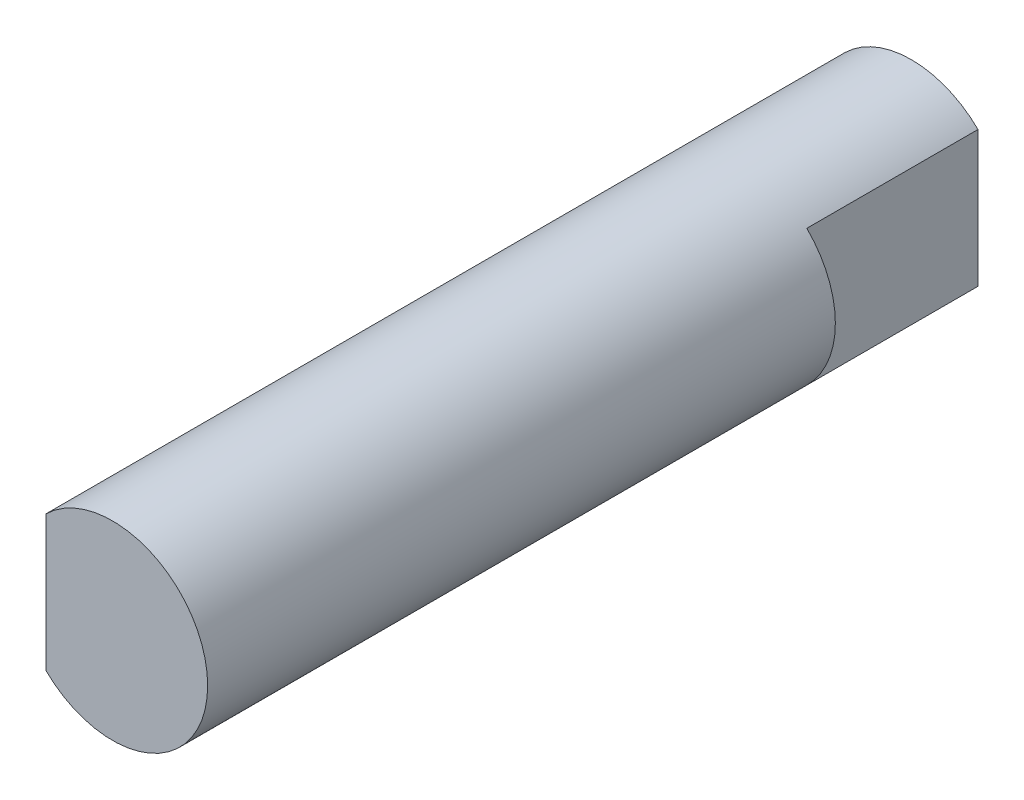
SolidWorks part; units mm, degrees
material "Cast Alloy Steel"
ref_plane "Front" through (0, 0, 0) normal (0, 0, 1) x (1, 0, 0)
ref_plane "Top" through (0, 0, 0) normal (0, 1, 0) x (1, 0, 0)
ref_plane "Right" through (0, 0, 0) normal (1, 0, 0) x (0, 0, -1)
sketch "Sketch1" plane through (0, 0, 0) normal (0, 0, 1) x (1, 0, 0)
  circle A0 centre (0, 0) radius 2.5
  dimension "D1" = 5
extrude "Boss-Extrude1" add sketch "Sketch1" along normal blind 21
sketch "Sketch2" plane through (0, 0, 0) normal (0, 0, -1) x (-1, 0, 0)
  line L2 (-1.75, -1.7854) -> (-1.75, 1.7854)
  line L4 (1.75, -1.7854) -> (1.75, 1.7854)
  line L5 (-1.75, -1.7854) -> (1.75, 1.7854) construction
  line L6 (-1.75, 1.7854) -> (1.75, -1.7854) construction
  circle A0 centre (0, 0) radius 2.5 construction
  arc A1 (-1.75, 1.7854) -> (-1.75, -1.7854) centre (0, 0) ccw
  arc A2 (1.75, 1.7854) -> (1.75, -1.7854) centre (0, 0) cw
  point P0 (0, 0)
  dimension "D1" = 3.5
extrude "Cut-Extrude2" cut sketch "Sketch2" against normal blind 4.5
sketch "Sketch3" plane through (0, 0, 0) normal (0, 0, -1) x (-1, 0, 0)
  circle A0 centre (0, 0) radius 1
  dimension "D1" = 2
extrude "Cut-Extrude3" cut sketch "Sketch3" against normal blind 6
cosmetic thread "Cosmetic Thread1" parameters "D2"=3
sketch "Sketch4" plane through (0, 0, 21) normal (0, 0, 1) x (1, 0, 0)
  line L2 (-1.75, -1.7854) -> (-1.75, 1.7854)
  arc A1 (-1.75, 1.7854) -> (-1.75, -1.7854) centre (0, 0) ccw
  point P0 (0, 0)
extrude "Cut-Extrude4" cut sketch "Sketch4" against normal blind 4.5
